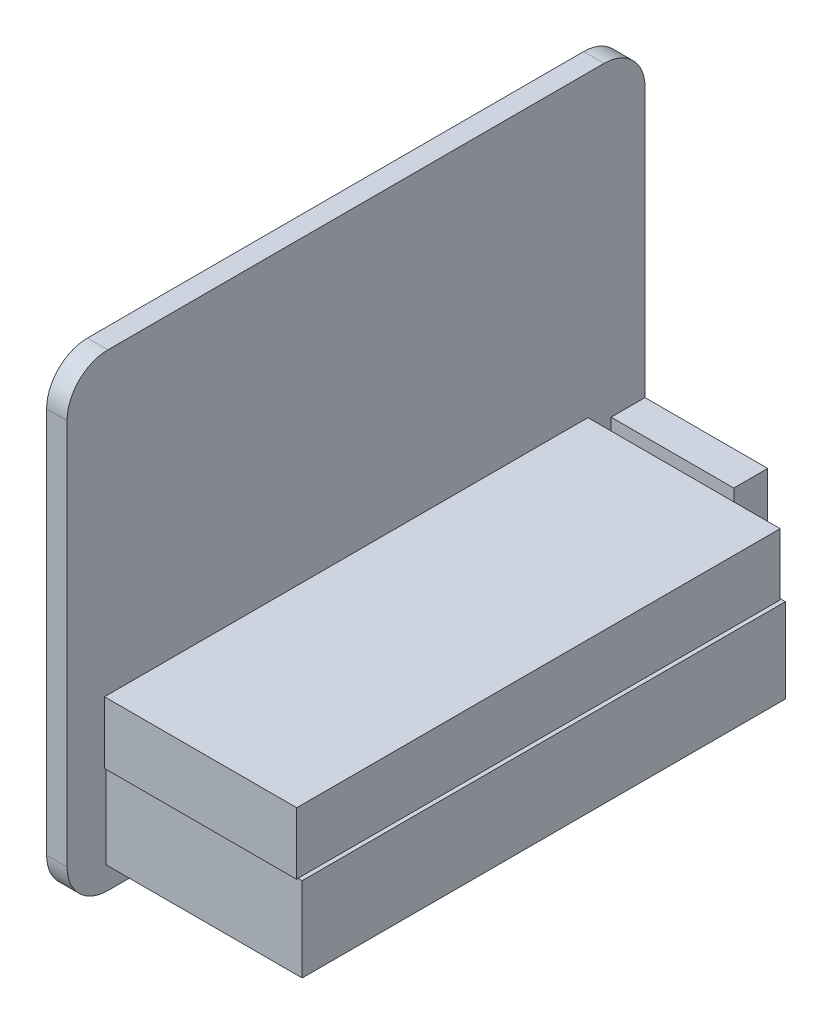
SolidWorks part; units mm, degrees
ref_plane "Front Plane" through (0, 0, 0) normal (0, 0, 1) x (1, 0, 0)
ref_plane "Top Plane" through (0, 0, 0) normal (0, 1, 0) x (1, 0, 0)
ref_plane "Right Plane" through (0, 0, 0) normal (1, 0, 0) x (0, 0, -1)
sketch "Sketch1" plane through (0, 0, 0) normal (1, 0, 0) x (0, 0, -1)
  line L1 (10, 0) -> (131.2922, 0)
  line L2 (0, -10) -> (0, -104.4885)
  line L3 (10, -114.4885) -> (131.2922, -114.4885)
  line L4 (141.2922, -10) -> (141.2922, -104.4885)
  arc A0 (131.2922, -114.4885) -> (141.2922, -104.4885) centre (131.2922, -104.4885) ccw
  arc A1 (10, -114.4885) -> (0, -104.4885) centre (10, -104.4885) cw
  arc A2 (10, 0) -> (0, -10) centre (10, -10) ccw
  arc A3 (131.2922, 0) -> (141.2922, -10) centre (131.2922, -10) cw
  dimension "D1" = 10
extrude "Boss-Extrude1" add sketch "Sketch1" along normal blind 5
sketch "Sketch2" plane through (5, 0, 0) normal (1, 0, 0) x (0, 0, -1)
  line L1 (127.3329, -73.0239) -> (9.1515, -73.0239)
  line L2 (127.3329, -73.0239) -> (127.3329, -88.1892)
  line L3 (127.3329, -88.1892) -> (9.1515, -88.1892)
  line L4 (9.1515, -73.0239) -> (9.1515, -88.1892)
extrude "Boss-Extrude4" add sketch "Sketch2" along normal blind 47
sketch "Sketch3" plane through (5, 0, 0) normal (1, 0, 0) x (0, 0, -1)
  line L1 (9.4854, -88.1192) -> (127.6118, -88.1192)
  line L2 (9.4854, -88.1192) -> (9.4854, -108.7357)
  line L3 (9.4854, -108.7357) -> (127.6118, -108.7357)
  line L4 (127.6118, -88.1192) -> (127.6118, -108.7357)
extrude "Boss-Extrude5" add sketch "Sketch3" along normal blind 48
sketch "Sketch4" plane through (5, 0, 0) normal (1, 0, 0) x (0, 0, -1)
  line L1 (132.9955, -102.0572) -> (141.2922, -102.0572)
  line L2 (132.9955, -102.0572) -> (132.9955, -75.7578)
  line L3 (132.9955, -75.7578) -> (141.2922, -75.7578)
  line L4 (141.2922, -102.0572) -> (141.2922, -75.7578)
extrude "Boss-Extrude6" add sketch "Sketch4" along normal blind 30
sketch "Sketch5" plane through (0, 0, -141.2922) normal (0, 0, -1) x (-1, 0, 0)
  line L0 (-25.4643, -97.9262) -> (-12.8104, -97.9262)
  line L2 (-31.1161, -91.5258) -> (-31.1161, -80.2755)
  line L3 (-31.1161, -80.2755) -> (-8.7312, -80.2755)
  line L4 (-8.7312, -90.2342) -> (-8.7312, -80.2755)
  line L5 (-12.8104, -97.9262) -> (-8.7312, -90.2342)
  line L6 (-31.1161, -91.5258) -> (-25.4643, -97.9262)
  point P4 (-25.4643, -97.9262)
extrude "Cut-Extrude3" cut sketch "Sketch5" against normal blind 7
sketch "Sketch6" plane through (0, 0, -134.2922) normal (0, 0, -1) x (-1, 0, 0)
  line L1 (-26.1502, -88.5216) -> (-23.9328, -88.5216)
  line L2 (-26.1502, -88.5216) -> (-26.1502, -86.6815)
  line L3 (-26.1502, -86.6815) -> (-23.9328, -86.6815)
  line L4 (-23.9328, -88.5216) -> (-23.9328, -86.6815)
  line L5 (-14.7425, -88.5216) -> (-12.174, -88.5216)
  line L6 (-14.7425, -88.5216) -> (-14.7425, -86.6815)
  line L7 (-14.7425, -86.6815) -> (-12.174, -86.6815)
  line L8 (-12.174, -88.5216) -> (-12.174, -86.6815)
  line L9 (-20.8183, -93.7688) -> (-18.1948, -93.7688)
  line L10 (-20.8183, -93.7688) -> (-20.8183, -91.9667)
  line L11 (-20.8183, -91.9667) -> (-18.1948, -91.9667)
  line L12 (-18.1948, -93.7688) -> (-18.1948, -91.9667)
extrude "Boss-Extrude7" add sketch "Sketch6" along normal blind 7
